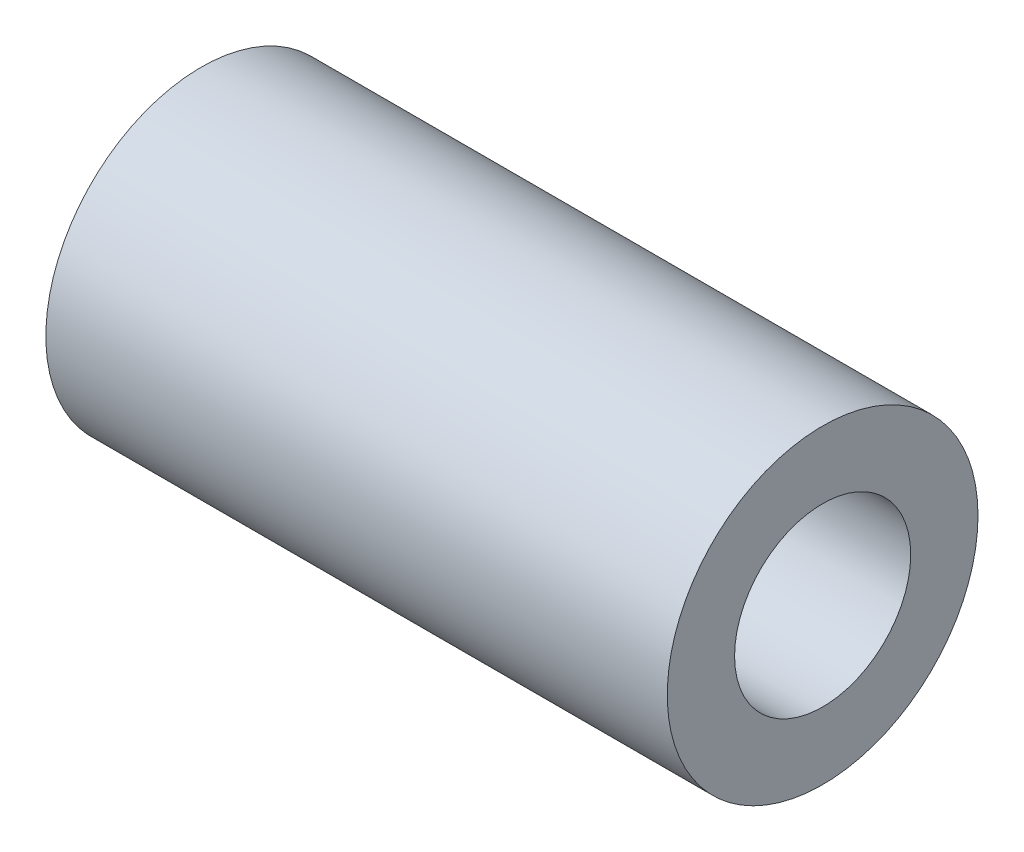
SolidWorks part; units mm, degrees
ref_plane "Front Plane" through (0, 0, 0) normal (0, 0, 1) x (1, 0, 0)
ref_plane "Top Plane" through (0, 0, 0) normal (0, 1, 0) x (1, 0, 0)
ref_plane "Right Plane" through (0, 0, 0) normal (1, 0, 0) x (0, 0, -1)
sketch "Sketch1" plane through (0, 0, 0) normal (1, 0, 0) x (0, 0, -1)
  circle A0 centre (0, 0) radius 1.8
  circle A1 centre (0, 0) radius 3.175
  dimension "D1" = 3.6
  dimension "D2" = 6.35
extrude "Boss-Extrude1" add sketch "Sketch1" along normal blind 12.7
